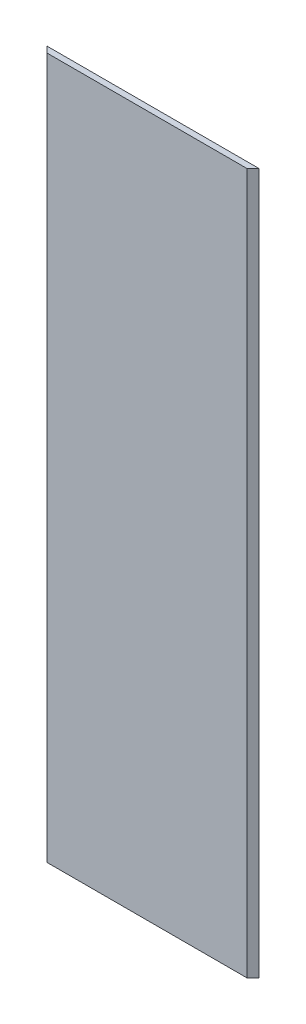
SolidWorks part; units mm, degrees
material "Balsa"
ref_plane "Front Plane" through (0, 0, 0) normal (1, 0, 0) x (0, 1, 0)
ref_plane "Top Plane" through (0, 0, 0) normal (0, 0, 1) x (0, 1, 0)
ref_plane "Right Plane" through (0, 0, 0) normal (0, 1, 0) x (-1, 0, 0)
sketch "Sketch1" plane through (0, 0, 0) normal (0, 0, 1) x (0, 1, 0)
  line L1 (-175, -50) -> (175, -50)
  line L2 (-175, -50) -> (-175, 50)
  line L3 (-175, 50) -> (175, 50)
  line L4 (175, -50) -> (175, 50)
  line L5 (-175, -50) -> (175, 50) construction
  line L6 (-175, 50) -> (175, -50) construction
  point P0 (0, 0)
  point P8 (154.451, 52.9603)
  point P9 (726.8568, -1215.7569)
  dimension "D1" = 350
  dimension "1" = 100
extrude "Boss-Extrude1" add sketch "Sketch1" along normal blind 3
sketch "Sketch2" plane through (0, -175, 0) normal (0, -1, 0) x (1, 0, 0)
  line L2 (-50, 3) -> (50, 3) construction
  line L5 (0, 0) -> (0, 3) construction
  line L9 (-50, 3) -> (-50, 0)
  line L10 (-50, 0) -> (-53, 0)
  line L11 (-50, 3) -> (-53, 0)
  line L12 (50, 3) -> (53, 0)
  line L13 (50, 0) -> (53, 0)
  line L14 (50, 3) -> (50, 0)
  dimension "D1" = 45
extrude "Boss-Extrude2" add sketch "Sketch2" against normal through all
